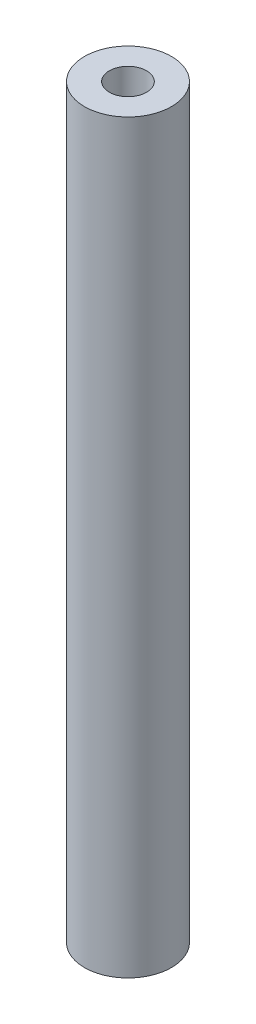
SolidWorks part; units mm, degrees
ref_plane "Front Plane" through (0, 0, 0) normal (0, 0, 1) x (1, 0, 0)
ref_plane "Top Plane" through (0, 0, 0) normal (0, 1, 0) x (1, 0, 0)
ref_plane "Right Plane" through (0, 0, 0) normal (1, 0, 0) x (0, 0, -1)
sketch "Sketch1" plane through (0, 0, 0) normal (0, 1, 0) x (1, 0, 0)
  circle A0 centre (0, 0) radius 3.5
  circle A1 centre (0, 0) radius 1.5
  dimension "D1" = 3
  dimension "D2" = 7
extrude "Boss-Extrude1" add sketch "Sketch1" along normal blind 60
